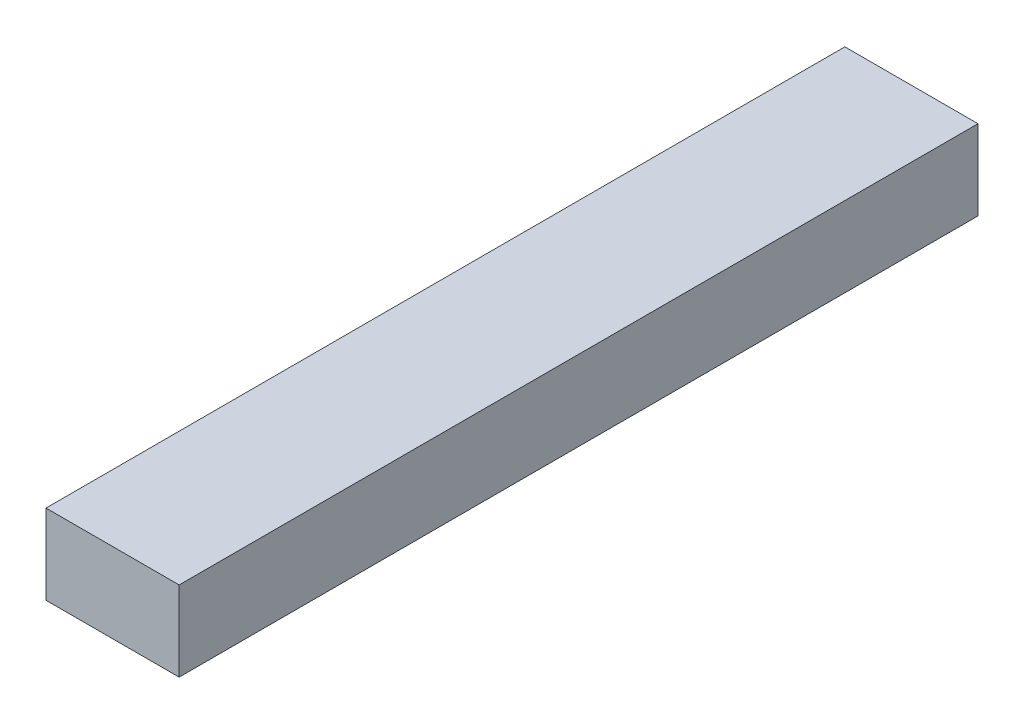
SolidWorks part; units mm, degrees
ref_plane "Front Plane" through (0, 0, 0) normal (0, 0, 1) x (1, 0, 0)
ref_plane "Top Plane" through (0, 0, 0) normal (0, 1, 0) x (1, 0, 0)
ref_plane "Right Plane" through (0, 0, 0) normal (1, 0, 0) x (0, 0, -1)
other "Configuration Table"
sketch "Sketch1" plane through (0, 0, 0) normal (0, 0, 1) x (1, 0, 0)
  line L1 (31.75, -19.05) -> (-31.75, -19.05)
  line L2 (31.75, -19.05) -> (31.75, 19.05)
  line L3 (31.75, 19.05) -> (-31.75, 19.05)
  line L4 (-31.75, -19.05) -> (-31.75, 19.05)
  line L5 (31.75, -19.05) -> (-31.75, 19.05) construction
  line L6 (31.75, 19.05) -> (-31.75, -19.05) construction
  point P0 (0, 0)
  dimension "D1" = 38.1
  dimension "D2" = 63.5
extrude "Boss-Extrude1" add sketch "Sketch1" along normal mid plane 381
